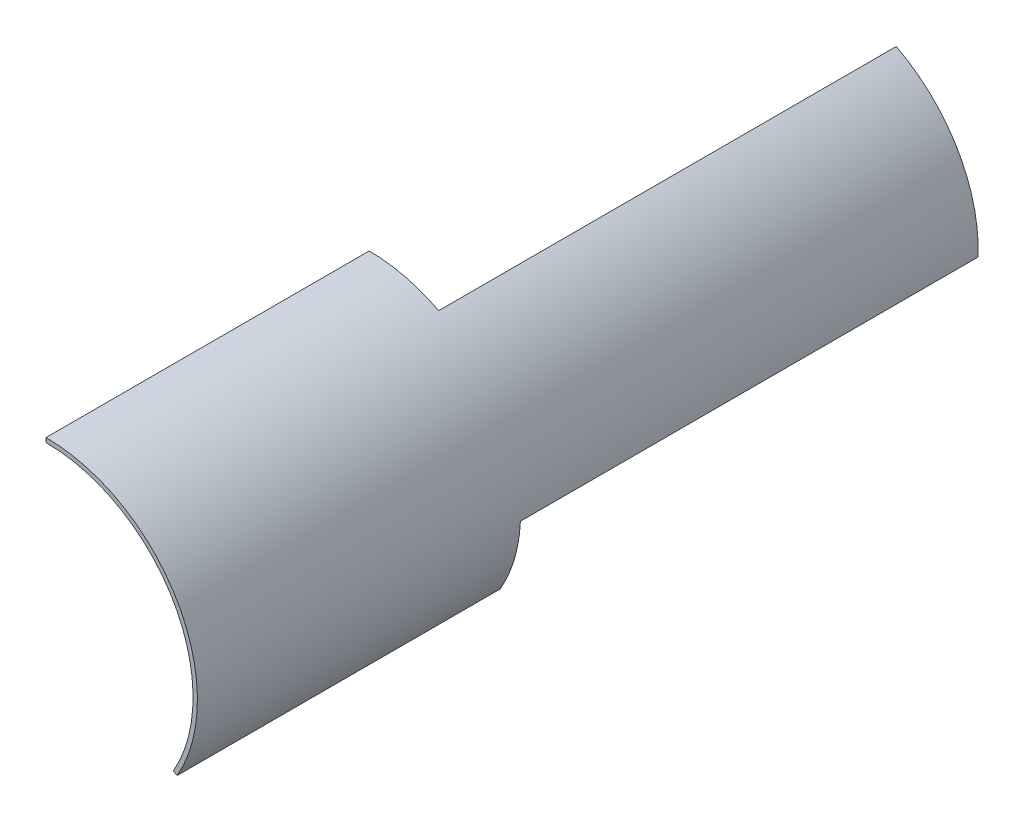
SolidWorks part; units mm, degrees
ref_plane "Front" through (0, 0, 0) normal (0, 0, 1) x (1, 0, 0)
ref_plane "Top" through (0, 0, 0) normal (0, 1, 0) x (1, 0, 0)
ref_plane "Right" through (0, 0, 0) normal (1, 0, 0) x (0, 0, -1)
sketch "Эскиз1" plane through (0, 0, 0) normal (1, 0, 0) x (0, 0, -1)
  line L0 (0, 41.7) -> (0, 40.5)
  line L1 (0, 40.5) -> (89, 40.5)
  line L2 (89, 40.5) -> (89, 41.7)
  line L3 (89, 41.7) -> (0, 41.7)
  line L4 (0, 0) -> (40.5832, 0) construction
  dimension "D1" = 1.2
  dimension "D2" = 40.5
  dimension "D3" = 89
revolve "Повернуть1" add sketch "Эскиз1" angle 120 about L4
ref_axis "Ось1" through (0, 0, -89) along (0, 0, 1)
ref_plane "Плоскость1" through (0, 0, 0) normal (0.5, -0.866, 0) x (0, 0, 1)
sketch "Эскиз3" plane through (0, 0, 0) normal (0.5, -0.866, 0) x (0, 0, 1)
  line L0 (-89, -40.5) -> (-215, -40.5)
  line L1 (-89, -20.85) -> (-89, -41.7) construction
  line L2 (-215, -40.5) -> (-215, -41.7)
  line L3 (-215, -41.7) -> (-89, -41.7)
  line L4 (-89, -41.7) -> (-89, -40.5)
  dimension "D1" = 1.2
  dimension "D2" = 40.5
  dimension "D3" = 126
revolve "Повернуть2" add sketch "Эскиз3" angle 33 about axis through (0, 0, -89) along (0, 0, 1) other way angle 33
sketch "Эскиз5" plane through (0, 0, -215) normal (0, 0, -1) x (-1, 0, 0)
  line L0 (-41.6552, -1.9327) -> (-39.9383, -1.4727)
  line L2 (-41.6552, -1.9327) -> (-41.9096, -3.6461)
  line L3 (-41.9096, -3.6461) -> (-38.9161, -3.4834)
  line L4 (-38.9161, -3.4834) -> (-39.9383, -1.4727)
  line L5 (-41.6429, -2.1824) -> (-40.4445, -2.1196) construction
  arc A0 (-18.9314, 37.155) -> (-41.6429, -2.1824) centre (0, 0) ccw construction
  dimension "D1" = 12
  dimension "D2" = 0.25
extrude "Вырез-Вытянуть4" cut sketch "Эскиз5" against normal up to surface (126 mm away) up to face at (37.1059, -15.9581, -89)
sketch "Эскиз6" plane through (0, 0, -215) normal (0, 0, -1) x (-1, 0, 0)
  line L0 (-18.8307, 35.856) -> (-19.8064, 39.4973)
  line L1 (-19.8064, 39.4973) -> (-16.0682, 39.4335)
  line L2 (-16.0682, 39.4335) -> (-15.3163, 34.0701)
  line L3 (-15.3163, 34.0701) -> (-18.8307, 35.856)
  line L5 (-18.9314, 37.155) -> (-18.3866, 36.0858) construction
  arc A0 (-18.3866, 36.0858) -> (-40.4678, -1.6146) centre (0, 0) ccw construction
  dimension "D1" = 12
  dimension "D2" = 0.5
extrude "Вырез-Вытянуть5" cut sketch "Эскиз6" against normal up to surface (126 mm away) up to face at (14.0624, 37.8739, -89)
